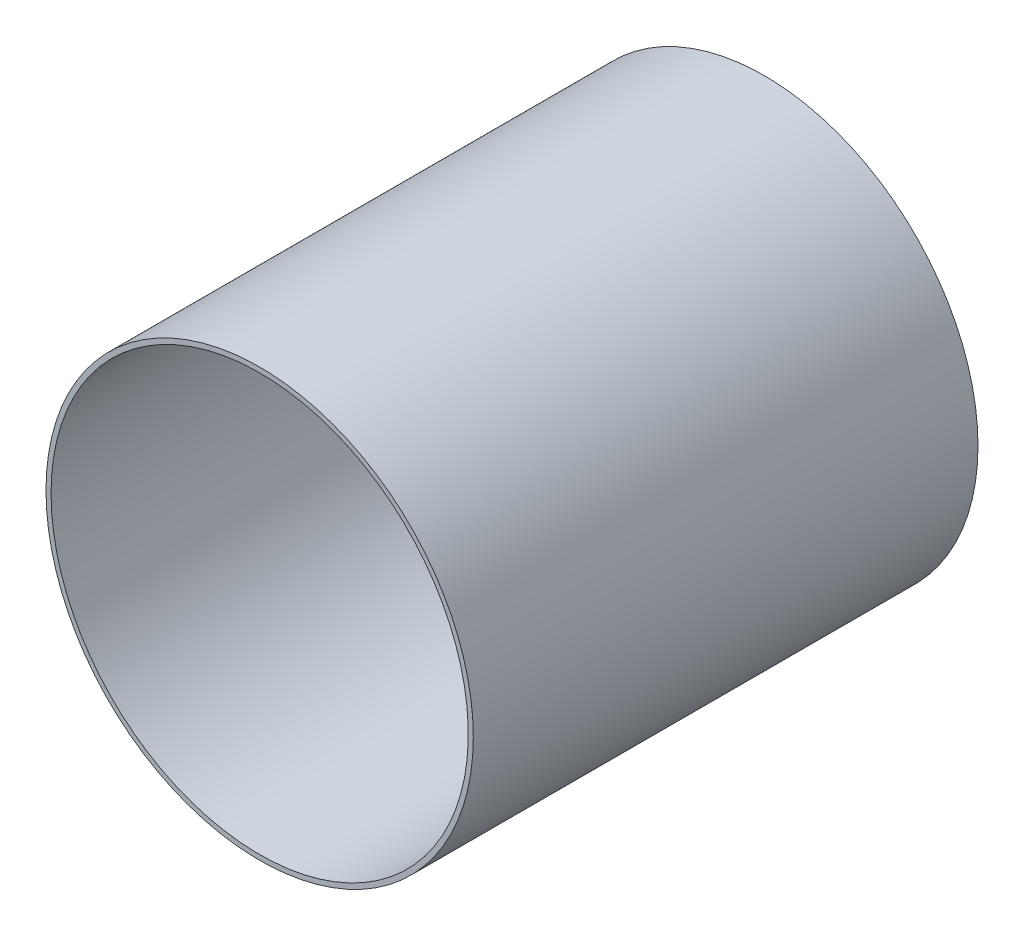
SolidWorks part; units mm, degrees
material "Corrugated Paper"
ref_plane "Front Plane" through (0, 0, 0) normal (0, 0, 1) x (1, 0, 0)
ref_plane "Top Plane" through (0, 0, 0) normal (0, 1, 0) x (1, 0, 0)
ref_plane "Right Plane" through (0, 0, 0) normal (1, 0, 0) x (0, 0, -1)
sketch "Sketch1" plane through (0, 0, 0) normal (0, 0, 1) x (1, 0, 0)
  circle A0 centre (0, 0) radius 31.5
  circle A1 centre (0, 0) radius 32.258
  dimension "D1" = 64.516
  dimension "D2" = 63
extrude "Boss-Extrude1" add sketch "Sketch1" along normal blind 76.2
